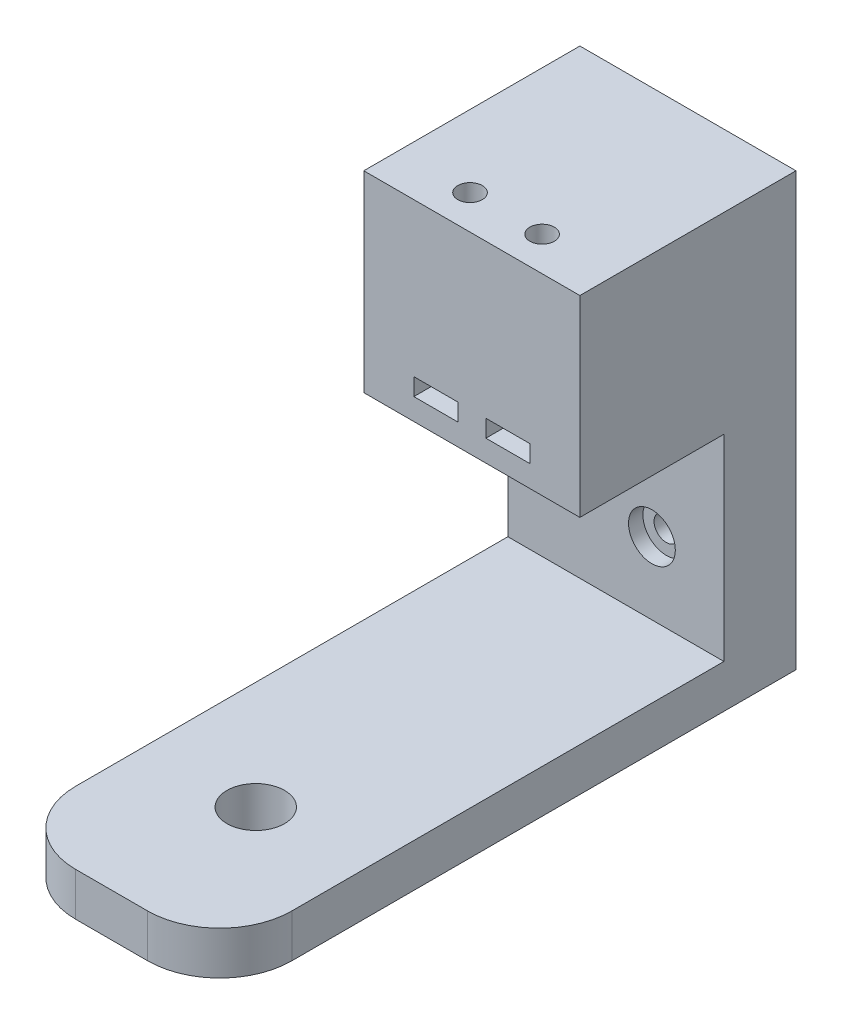
SolidWorks part; units mm, degrees
ref_plane "Plan de face" through (0, 0, 0) normal (0, 0, 1) x (1, 0, 0)
ref_plane "Plan de dessus" through (0, 0, 0) normal (0, 1, 0) x (1, 0, 0)
ref_plane "Plan de droite" through (0, 0, 0) normal (1, 0, 0) x (0, 0, -1)
sketch "Esquisse1" plane through (0, 0, 0) normal (0, 0, 1) x (1, 0, 0)
  line L1 (0, 0) -> (30, 0)
  line L2 (0, 0) -> (0, 60)
  line L3 (0, 60) -> (30, 60)
  line L4 (30, 0) -> (30, 60)
  dimension "D1" = 30
  dimension "D2" = 60
extrude "Boss.-Extru.1" add sketch "Esquisse1" along normal blind 10
sketch "Esquisse2" plane through (0, 0, 10) normal (0, 0, 1) x (1, 0, 0)
  line L0 (30, 0) -> (30, 60) construction
  line L1 (0, 0) -> (30, 0) construction
  line L2 (0, 60) -> (0, 0) construction
  line L3 (30, 0) -> (30, 6)
  line L4 (0, 0) -> (30, 0)
  line L5 (0, 6) -> (0, 0)
  line L6 (0, 6) -> (30, 6)
  dimension "D1" = 6
extrude "Boss.-Extru.2" add sketch "Esquisse2" along normal blind 70
sketch "Esquisse3" plane through (0, 0, 0) normal (0, -1, 0) x (1, 0, 0)
  line L0 (0, 80) -> (0, 0) construction
  line L1 (0, 0) -> (30, 0) construction
  circle A0 centre (15, 60) radius 4
  dimension "D3" = 8
  dimension "D1" = 15
  dimension "D2" = 60
extrude "Enlèv. mat.-Extru.1" cut sketch "Esquisse3" against normal up to surface (6 mm away) up to face at (15, 6, 45)
sketch "Esquisse4" plane through (0, 0, 10) normal (0, 0, 1) x (1, 0, 0)
  line L0 (30, 6) -> (30, 60) construction
  line L1 (30, 33.32) -> (30, 60)
  line L2 (0, 60) -> (0, 6) construction
  line L3 (30, 60) -> (0, 60) construction
  line L4 (0, 60) -> (0, 33.32)
  line L5 (30, 60) -> (0, 60)
  line L6 (0, 33.32) -> (30, 33.32)
  line L8 (30, 6) -> (0, 6) construction
  dimension "D1" = 27.32
extrude "Boss.-Extru.3" add sketch "Esquisse4" along normal blind 20
sketch "Esquisse5" plane through (0, 33.32, 0) normal (0, -1, 0) x (1, 0, 0)
  line L0 (0, 30) -> (0, 10) construction
  line L2 (0, 30) -> (30, 30) construction
  circle A0 centre (10, 25.25) radius 2.2
  circle A1 centre (20, 25.25) radius 2.2
  dimension "D3" = 4.4
  dimension "D4" = 4.4
  dimension "D1" = 10
  dimension "D2" = 10
  dimension "D5" = 4.75
  dimension "D6" = 4.75
hole_wizard "Dégagement M31" positions "Esquisse8" profile "Esquisse7" hole size "M3" standard "ISO"
sketch "Esquisse8" plane through (0, 33.32, 0) normal (0, -1, 0) x (-1, 0, 0)
  point P0 (-10, -25.25)
  point P3 (-20, -25.25)
sketch "Esquisse7" plane through (10, 33.32, 25.25) normal (1, 0, 0) x (0, 0, -1)
  line L0 (0, 0) -> (0, 27.7015)
  line L1 (0, 27.7015) -> (1.7, 26.68)
  line L2 (1.7, 26.68) -> (1.7, 0)
  line L5 (1.7, 0) -> (0, 0)
  line L10 (0, 27.7015) -> (-1.7, 26.68) construction
  line L11 (0, -6.35) -> (0, 107.95) construction
  dimension "Diamètre du perçage" = 3.4
  dimension "Profondeur du perçage" = 26.68
  dimension "Angle de pointe" = 118
sketch "Esquisse9" plane through (0, 0, 10) normal (0, 0, 1) x (1, 0, 0)
  line L0 (0, 33.32) -> (0, 6) construction
  line L1 (30, 6) -> (30, 33.32) construction
  line L2 (30, 6) -> (0, 6) construction
  line L3 (0, 33.32) -> (30, 33.32) construction
  circle A1 centre (20, 16) radius 1.5
  circle A2 centre (10, 23.32) radius 1.5
  dimension "D2" = 3
  dimension "D4" = 3
  dimension "D1" = 10
  dimension "D3" = 10
  dimension "D5" = 10
  dimension "D6" = 10
hole_wizard "Chambrage pour tête cylindrique fendue M31" positions "Esquisse10" profile "Esquisse12" counterbore size "M3" standard "ISO"
sketch "Esquisse10" plane through (0, 0, 10) normal (0, 0, 1) x (1, 0, 0)
  point P0 (10, 23.32)
  point P3 (20, 16)
sketch "Esquisse12" plane through (10, 23.32, 10) normal (1, 0, 0) x (0, -1, 0)
  line L0 (0, 0) -> (0, 11.0215)
  line L1 (0, 11.0215) -> (1.7, 10)
  line L2 (1.7, 10) -> (1.7, 2)
  line L3 (1.7, 2) -> (3.25, 2)
  line L4 (3.25, 2) -> (3.25, 0)
  line L5 (3.25, 0) -> (0, 0)
  line L10 (0, 11.0215) -> (-1.7, 10) construction
  line L11 (0, -6.35) -> (0, 107.95) construction
  dimension "Diamètre du perçage" = 3.4
  dimension "Profondeur du perçage" = 10
  dimension "Diamètre du chambrage" = 6.5
  dimension "Profondeur du chambrage" = 2
  dimension "Angle de pointe" = 118
fillet "Congé1" radius 10 2 edges at (30, 3, 80) (0, 3, 80)
sketch "Esquisse13" plane through (0, 0, 30) normal (0, 0, 1) x (1, 0, 0)
  line L0 (0, 33.32) -> (30, 33.32) construction
  line L1 (6.95, 38.72) -> (13.05, 38.72)
  line L2 (6.95, 38.72) -> (6.95, 36.32)
  line L3 (6.95, 36.32) -> (13.05, 36.32)
  line L4 (13.05, 38.72) -> (13.05, 36.32)
  line L5 (23.05, 38.72) -> (16.95, 38.72)
  line L6 (23.05, 38.72) -> (23.05, 36.32)
  line L7 (23.05, 36.32) -> (16.95, 36.32)
  line L8 (16.95, 38.72) -> (16.95, 36.32)
  line L9 (0, 60) -> (0, 33.32) construction
  line L10 (30, 33.32) -> (30, 60) construction
  point P10 (10, 38.72)
  point P13 (20, 38.72)
  dimension "D1" = 3
  dimension "D2" = 3
  dimension "D3" = 10
  dimension "D4" = 10
  dimension "D5" = 6.1
  dimension "D6" = 6.1
  dimension "D7" = 2.4
  dimension "D8" = 2.4
extrude "Enlèv. mat.-Extru.2" cut sketch "Esquisse13" against normal blind 8.45
equation "\"D4@Esquisse5\"=\"D3@Esquisse5\""
equation "\"D6@Esquisse5\"=\"D5@Esquisse5\""
